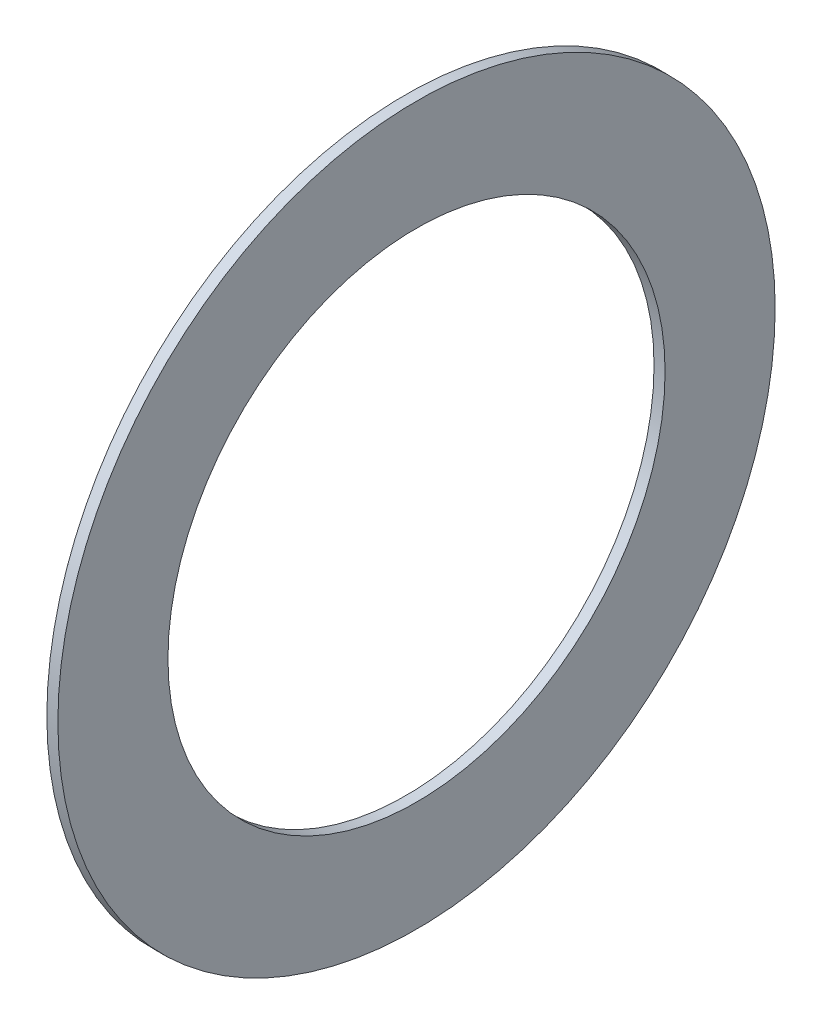
SolidWorks part; units mm, degrees
material "AISI 304"
ref_plane "Front Plane" through (0, 0, 0) normal (0, 0, 1) x (1, 0, 0)
ref_plane "Top Plane" through (0, 0, 0) normal (0, 1, 0) x (1, 0, 0)
ref_plane "Right Plane" through (0, 0, 0) normal (1, 0, 0) x (0, 0, -1)
sketch "Sketch1" plane through (0, 0, 0) normal (1, 0, 0) x (0, 0, -1)
  circle A0 centre (0, 0) radius 32.5
  circle A1 centre (0, 0) radius 22.5 construction
  circle A2 centre (0, 0) radius 22.525
  dimension "OD" = 65
  dimension "For Shaft Diameter" = 45
  dimension "ID" = 45.05
sketch "Sketch2" plane through (0, 0, 0) normal (0, 0, 1) x (1, 0, 0)
  line L0 (0.5, 0) -> (-0.5, 0) construction
  line L1 (0.5, -32.5) -> (-0.5, -32.5) construction
  line L2 (0.5, -32.5) -> (0.5, 32.5) construction
  line L3 (0.5, 32.5) -> (-0.5, 32.5) construction
  line L4 (-0.5, -32.5) -> (-0.5, 32.5) construction
  point P6 (0, 32.5)
  point P9 (0, -32.5)
  dimension "Thickness" = 1
sketch "Sketch3" plane through (0, 0, 0) normal (1, 0, 0) x (0, 0, -1)
  circle A1 centre (0, 0) radius 32.5 construction
  circle A3 centre (0, 0) radius 32.5
  circle A4 centre (0, 0) radius 22.525 construction
  circle A5 centre (0, 0) radius 22.525
extrude "Boss-Extrude1" add sketch "Sketch3" along normal up to vertex (0.5 mm away) and the other way up to vertex (0.5 mm away) up to point (0.5, 32.5, 0) other way up to point (-0.5, 32.5, 0)
